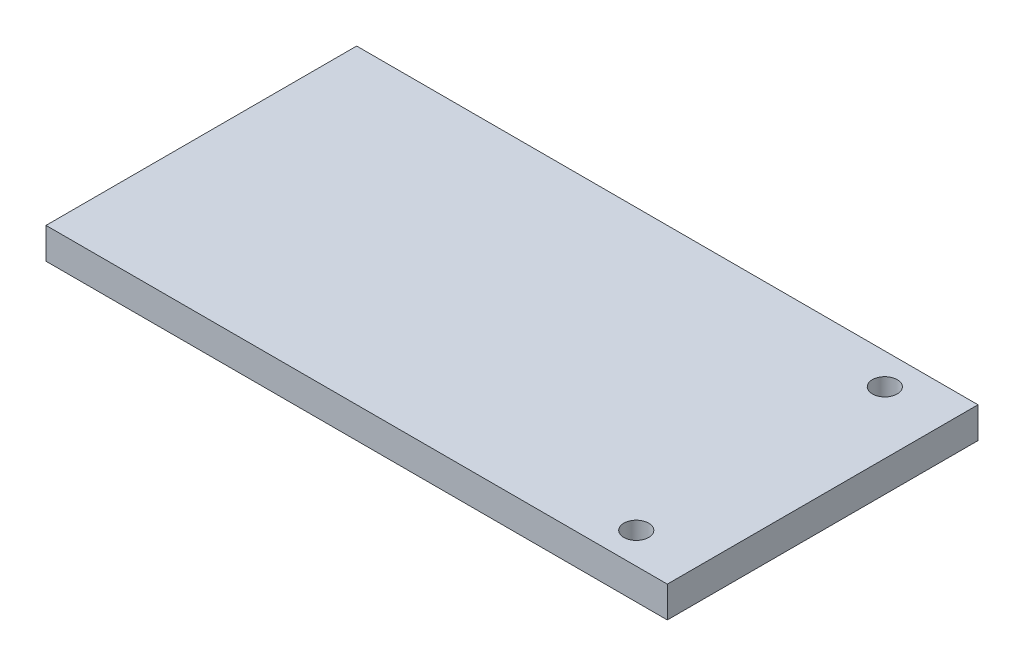
SolidWorks part; units mm, degrees
ref_plane "前视基准面" through (0, 0, 0) normal (0, 0, 1) x (1, 0, 0)
ref_plane "上视基准面" through (0, 0, 0) normal (0, 1, 0) x (1, 0, 0)
ref_plane "右视基准面" through (0, 0, 0) normal (1, 0, 0) x (0, 0, -1)
sketch "草图1" plane through (0, 0, 0) normal (0, 1, 0) x (1, 0, 0)
  line L0 (40, 20) -> (40, -20)
  line L1 (-50, 25) -> (50, 25)
  line L2 (-50, 25) -> (-50, -25)
  line L3 (-50, -25) -> (50, -25)
  line L4 (50, 25) -> (50, -25)
  line L5 (-50, 25) -> (50, -25) construction
  line L6 (-50, -25) -> (50, 25) construction
  circle A0 centre (40, 20) radius 2
  circle A1 centre (40, -20) radius 2
  point P0 (0, 0)
  dimension "D1" = 50
  dimension "D2" = 100
  dimension "D3" = 40
  dimension "D4" = 5
  dimension "D5" = 5
extrude "凸台-拉伸1" add sketch "草图1" along normal blind 5
